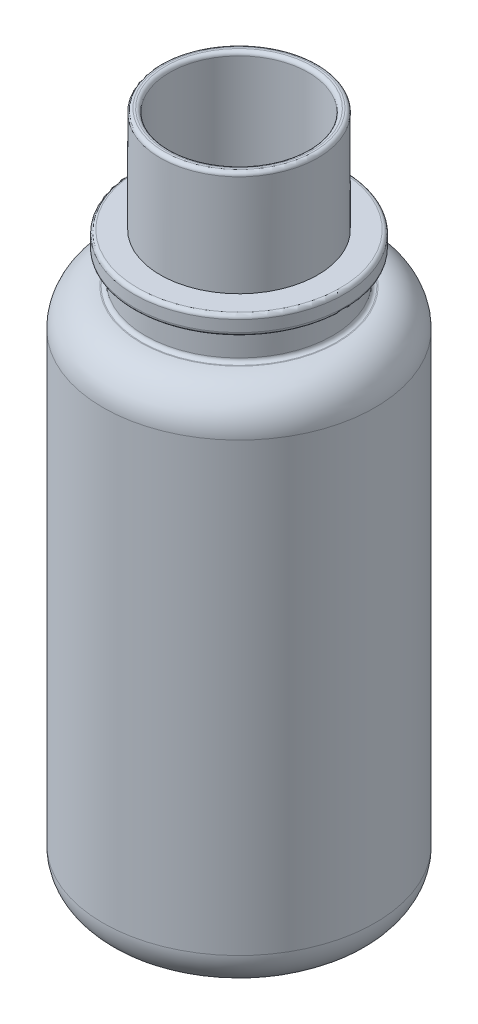
SolidWorks part; units mm, degrees
ref_plane "Front Plane" through (0, 0, 0) normal (0, 0, 1) x (1, 0, 0)
ref_plane "Top Plane" through (0, 0, 0) normal (0, 1, 0) x (1, 0, 0)
ref_plane "Right Plane" through (0, 0, 0) normal (1, 0, 0) x (0, 0, -1)
sketch "Sketch1" plane through (0, 0, 0) normal (0, 0, 1) x (1, 0, 0)
  line L0 (0, 0) -> (0, 91.44) construction
  line L1 (0, 0) -> (18.415, 0)
  line L2 (18.415, 0) -> (18.415, 70.612)
  line L3 (18.415, 70.612) -> (12.7, 70.612)
  line L4 (12.7, 70.612) -> (12.7, 74.676)
  line L5 (12.7, 74.676) -> (14.224, 74.676)
  line L6 (14.224, 74.676) -> (14.224, 77.216)
  line L7 (10.668, 77.216) -> (14.224, 77.216)
  line L8 (10.668, 77.216) -> (10.668, 91.44)
  line L9 (10.668, 91.44) -> (0, 91.44) construction
  line L10 (9.398, 91.44) -> (9.398, 75.946)
  line L11 (9.398, 75.946) -> (11.43, 73.4643)
  line L12 (11.43, 73.4643) -> (11.43, 69.342)
  line L13 (11.43, 69.342) -> (17.145, 69.342)
  line L14 (17.145, 69.342) -> (17.145, 1.27)
  line L15 (17.145, 1.27) -> (0, 1.27)
  line L16 (9.398, 91.44) -> (10.668, 91.44)
  line L17 (0, 1.27) -> (0, 0)
  point P11 (14.224, 75.946)
  dimension "D1" = 91.44
  dimension "D2" = 70.612
  dimension "D3" = 12.7
  dimension "D4" = 18.415
  dimension "D5" = 4.064
  dimension "D6" = 14.224
  dimension "D8" = 10.668
  dimension "D7" = 2.54
  dimension "D9" = 1.27
  dimension "D10" = 1.27
  dimension "D11" = 1.27
  dimension "D12" = 1.27
  dimension "D13" = 1.27
revolve "Revolve1" add sketch "Sketch1" angle 360 about L0
fillet "Fillet1" radius 5.08 4 edges at (0, 70.612, -18.415) (0, 0, -18.415) (0, 1.27, -17.145) (0, 69.342, -17.145)
fillet "Fillet2" radius 0.508 8 edges at (0, 91.44, -10.668) (0, 91.44, -9.398) (0, 75.946, -9.398) (0, 73.4643, -11.43) (0, 69.342, -11.43) (0, 70.612, -12.7) (0, 74.676, -14.224) (0, 77.216, -14.224)
equation "\"wall\"=0.05"
equation "\"D9@Sketch1\"=\"wall\""
equation "\"D10@Sketch1\"=\"wall\""
equation "\"D11@Sketch1\"=\"wall\""
equation "\"D12@Sketch1\"=\"wall\""
equation "\"D13@Sketch1\"=\"wall\""
